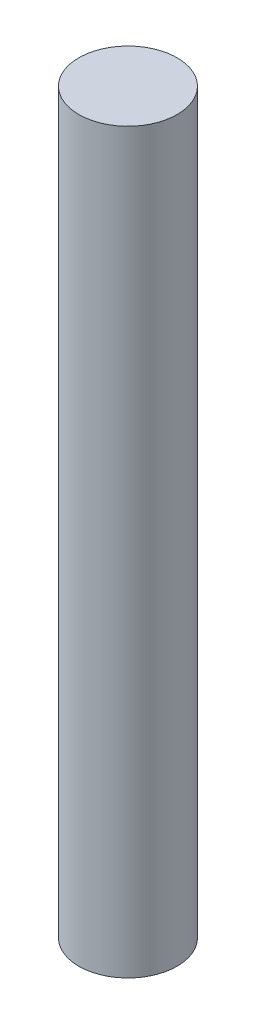
SolidWorks part; units mm, degrees
ref_plane "Front Plane" through (0, 0, 0) normal (0, 0, 1) x (1, 0, 0)
ref_plane "Top Plane" through (0, 0, 0) normal (0, 1, 0) x (1, 0, 0)
ref_plane "Right Plane" through (0, 0, 0) normal (1, 0, 0) x (0, 0, -1)
sketch "Sketch1" plane through (0, 0, 0) normal (0, 1, 0) x (1, 0, 0)
  circle A0 centre (0, 0) radius 5
  dimension "D1" = 10
extrude "Boss-Extrude1" add sketch "Sketch1" along normal blind 75
